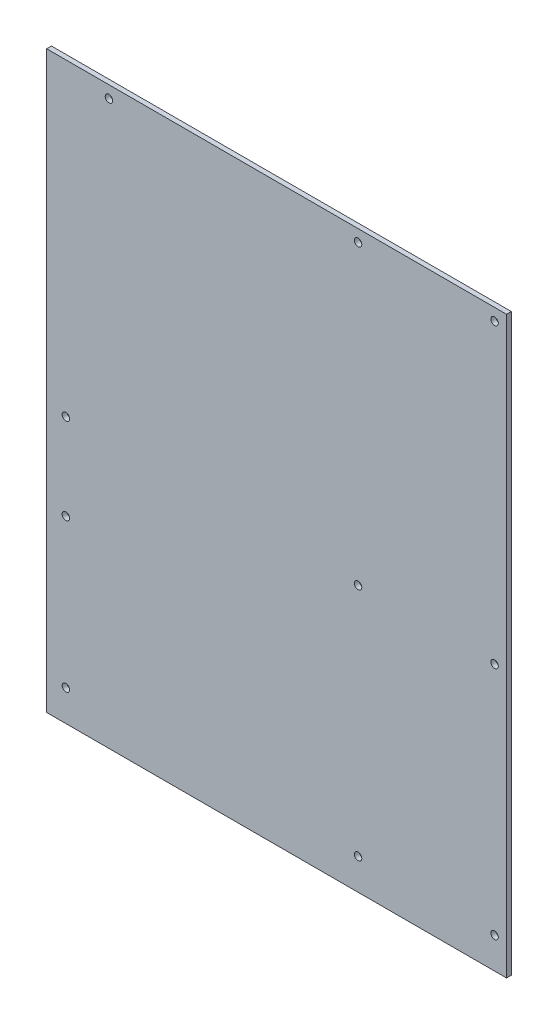
SolidWorks part; units mm, degrees
ref_plane "정면" through (0, 0, 0) normal (0, 0, 1) x (1, 0, 0)
ref_plane "윗면" through (0, 0, 0) normal (0, 1, 0) x (1, 0, 0)
ref_plane "우측면" through (0, 0, 0) normal (1, 0, 0) x (0, 0, -1)
sketch "스케치1" plane through (0, 0, 0) normal (0, 0, 1) x (1, 0, 0)
  line L0 (165.1, 140.97) -> (165.1, 16.51) construction
  line L1 (0, 0) -> (243.84, 0)
  line L2 (0, 0) -> (0, 304.8)
  line L3 (0, 304.8) -> (243.84, 304.8)
  line L4 (243.84, 0) -> (243.84, 304.8)
  line L5 (10.16, 298.45) -> (237.49, 298.45) construction
  line L6 (10.16, 298.45) -> (10.16, 16.51) construction
  line L7 (10.16, 16.51) -> (237.49, 16.51) construction
  line L8 (237.49, 298.45) -> (237.49, 16.51) construction
  line L9 (10.16, 298.45) -> (165.1, 298.45) construction
  line L10 (10.16, 298.45) -> (10.16, 140.97) construction
  line L11 (10.16, 140.97) -> (165.1, 140.97) construction
  line L12 (165.1, 298.45) -> (165.1, 140.97) construction
  line L13 (165.1, 140.97) -> (237.49, 140.97) construction
  circle A0 centre (33.02, 298.45) radius 1.9812
  circle A1 centre (165.1, 298.45) radius 1.9812
  circle A2 centre (237.49, 298.45) radius 1.9812
  circle A3 centre (237.49, 140.97) radius 1.9812
  circle A4 centre (165.1, 140.97) radius 1.9812
  circle A5 centre (10.16, 140.97) radius 1.9812
  circle A6 centre (10.16, 16.51) radius 1.9812
  circle A7 centre (165.1, 16.51) radius 1.9812
  circle A8 centre (237.49, 16.51) radius 1.9812
  circle A9 centre (10.16, 95.25) radius 1.9812
  dimension "D3" = 3.9624
  dimension "D1" = 304.8
  dimension "D2" = 243.84
  dimension "D4" = 16.51
  dimension "D5" = 227.33
  dimension "D6" = 10.16
  dimension "D7" = 281.94
  dimension "D8" = 154.94
  dimension "D9" = 124.46
  dimension "D10" = 78.74
  dimension "D11" = 22.86
extrude "보스-돌출1" add sketch "스케치1" along normal blind 2.54
